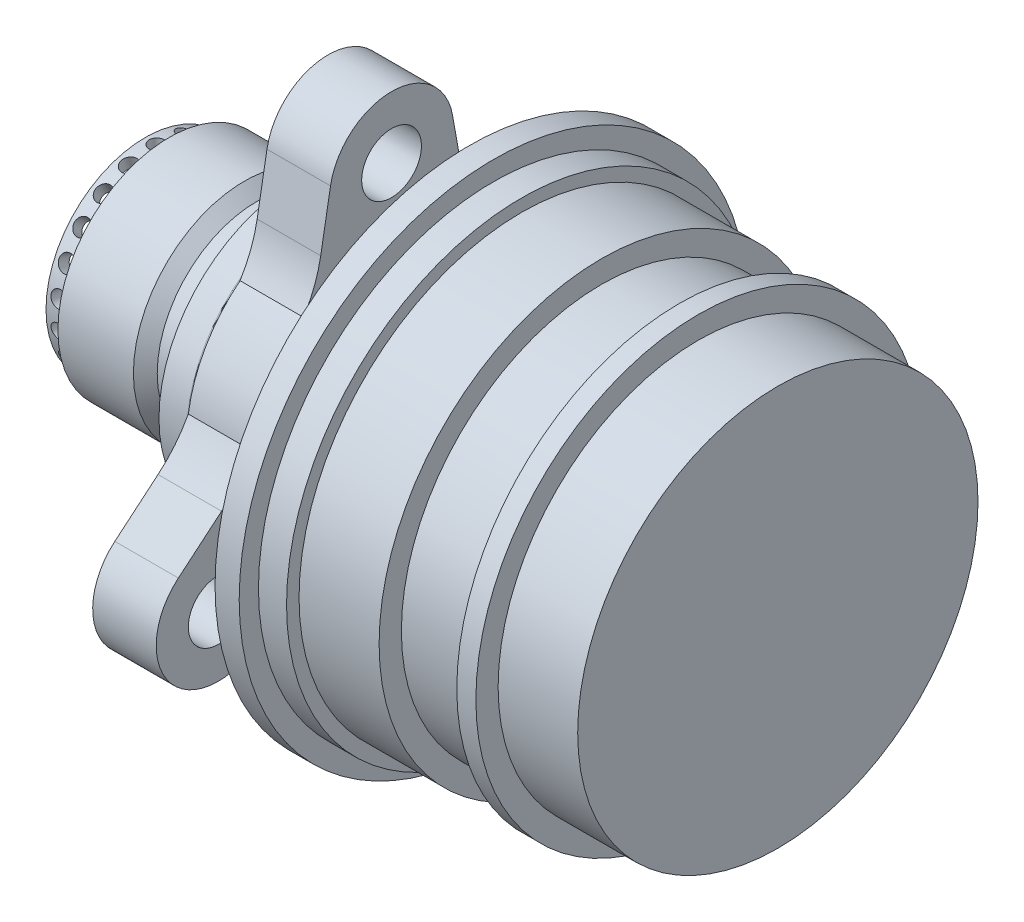
SolidWorks part; units mm, degrees
ref_plane "Front Plane" through (0, 0, 0) normal (0, 0, 1) x (1, 0, 0)
ref_plane "Top Plane" through (0, 0, 0) normal (0, 1, 0) x (1, 0, 0)
ref_plane "Right Plane" through (0, 0, 0) normal (1, 0, 0) x (0, 0, -1)
sketch "Sketch1" plane through (0, 0, 0) normal (0, 0, 1) x (1, 0, 0)
  line L2 (-605.6405, 247.65) -> (-589.6405, 247.65)
  line L3 (-644.3015, 255.5875) -> (-644.3015, 231.4258)
  line L5 (-570.3065, 243.1999) -> (-554.4065, 243.1999)
  line L9 (-605.6405, 247.65) -> (-605.6405, 250.15)
  line L11 (-554.4065, 243.1999) -> (-554.4065, 203.2)
  line L12 (-644.3015, 255.5875) -> (-631.6015, 255.5875)
  line L21 (-676.0515, 225.425) -> (-676.0515, 223.0437)
  line L22 (-676.0515, 223.0437) -> (-680.814, 223.0438)
  line L23 (-680.814, 223.0438) -> (-680.814, 220.6625)
  line L28 (-616.0785, 254) -> (-611.2525, 254)
  line L29 (-611.2525, 254) -> (-611.2525, 250.15)
  line L30 (-611.2525, 250.15) -> (-605.6405, 250.15)
  line L39 (-650.6515, 230.632) -> (-645.0952, 230.632)
  line L42 (-625.2515, 225.425) -> (-622.4285, 225.425)
  line L43 (-631.6015, 255.5875) -> (-631.6015, 231.775)
  line L44 (-616.0785, 254) -> (-616.0785, 231.775)
  line L45 (-655.414, 223.0437) -> (-658.589, 223.0437)
  line L46 (-658.589, 223.0437) -> (-660.9702, 225.425)
  line L47 (-650.6515, 227.8062) -> (-650.6515, 230.632)
  line L48 (-570.3065, 243.1999) -> (-570.3065, 247.65)
  line L50 (-574.1165, 247.65) -> (-574.1165, 243.1999)
  line L52 (-589.6405, 243.1999) -> (-589.6405, 247.65)
  line L53 (-660.9702, 225.425) -> (-676.0515, 225.425)
  line L54 (-680.814, 220.6625) -> (-618.6185, 220.6625)
  line L55 (-616.0785, 218.1225) -> (-616.0785, 203.2)
  line L56 (-616.0785, 203.2) -> (-554.4065, 203.2)
  line L57 (-618.6185, 220.6625) -> (-616.0785, 220.6625)
  line L58 (-616.0785, 220.6625) -> (-616.0785, 218.1225)
  line L59 (-574.1165, 247.65) -> (-570.3065, 247.65)
  line L60 (-589.6405, 243.1999) -> (-574.1165, 243.1999)
  arc A0 (-645.0952, 230.632) -> (-644.3015, 231.4258) centre (-645.0952, 231.4258) ccw
  arc A1 (-655.414, 223.0437) -> (-650.6515, 227.8062) centre (-655.414, 227.8062) ccw
  arc A2 (-622.4285, 225.425) -> (-616.0785, 231.775) centre (-622.4285, 231.775) ccw
  arc A3 (-631.6015, 231.775) -> (-625.2515, 225.425) centre (-625.2515, 231.775) ccw
  point P8 (-597.6405, 247.65)
  point P16 (-562.3565, 243.1999)
  point P32 (-613.6655, 254)
  dimension "D5" = 0.7937
  dimension "D10" = 4.7625
  dimension "D19" = 6.35
  dimension "D20" = 2.54
  dimension "D1" = 16
  dimension "D2" = 39.9999
  dimension "D3" = 15.9
  dimension "D4" = 12.7
  dimension "D6" = 17.4625
  dimension "D8" = 19.8438
  dimension "D9" = 27.432
  dimension "D11" = 4.7625
  dimension "D12" = 25.4
  dimension "D13" = 135
  dimension "D14" = 3.175
  dimension "D15" = 22.225
  dimension "D16" = 52.3875
  dimension "D17" = 4.826
  dimension "D18" = 50.8
  dimension "D21" = 2.5
  dimension "D22" = 44.45
  dimension "D23" = 5.612
  dimension "D27" = 3.81
  dimension "D28" = 2.54
revolve "Revolve1" add sketch "Sketch1" angle 360 about L56
sketch "Sketch2" plane through (-644.3015, 0, 0) normal (-1, 0, 0) x (0, 0, 1)
  line L0 (0, 243.2) -> (0, 203.2) construction
  line L1 (0, 203.2) -> (34.641, 183.2) construction
  line L2 (34.641, 183.2) -> (0, 203.2) construction
  line L3 (0, 203.2) -> (-34.641, 183.2) construction
  circle A0 centre (0, 203.2) radius 40 construction
  circle A1 centre (0, 243.2) radius 5.975
  circle A2 centre (-34.641, 183.2) radius 5.975
  circle A3 centre (34.641, 183.2) radius 5.975
  dimension "D1" = 80
  dimension "D2" = 11.95
  dimension "D5" = 11.95
  dimension "D6" = 11.95
  dimension "D3" = 120
  dimension "D4" = 120
extrude "Cut-Extrude1" cut sketch "Sketch2" against normal up to next
sketch "Sketch4" plane through (-644.3015, 0, 0) normal (-1, 0, 0) x (0, 0, 1)
  line L0 (-14.1576, 234.2452) -> (-12.1993, 245.3511)
  line L1 (12.1993, 245.3511) -> (14.1576, 234.2452)
  line L2 (0, 243.2) -> (0, 203.2) construction
  line L3 (33.9647, 199.9382) -> (42.6035, 192.6894)
  line L4 (30.4042, 171.5596) -> (19.8071, 175.4166)
  line L5 (-19.8071, 175.4166) -> (-30.4042, 171.5596)
  line L6 (-42.6035, 192.6894) -> (-33.9647, 199.9382)
  arc A0 (-5.774, 176.3795) -> (5.774, 176.3795) centre (0, 203.2) ccw
  arc A1 (-12.1993, 245.3511) -> (12.1993, 245.3511) centre (0, 243.2) cw
  arc A2 (14.1576, 234.2452) -> (20.3402, 221.6107) centre (39.1717, 238.6558) ccw
  arc A3 (-14.1576, 234.2452) -> (-20.3402, 221.6107) centre (-39.1717, 238.6558) cw
  arc A4 (33.9647, 199.9382) -> (26.1143, 211.6098) centre (50.2915, 219.3958) cw
  arc A5 (42.6035, 192.6894) -> (30.4042, 171.5596) centre (34.641, 183.2) cw
  arc A6 (19.8071, 175.4166) -> (5.774, 176.3795) centre (11.1198, 151.5484) ccw
  arc A7 (-19.8071, 175.4166) -> (-5.774, 176.3795) centre (-11.1198, 151.5484) cw
  arc A8 (-30.4042, 171.5596) -> (-42.6035, 192.6894) centre (-34.641, 183.2) cw
  arc A9 (-33.9647, 199.9382) -> (-26.1143, 211.6098) centre (-50.2915, 219.3958) ccw
  arc A10 (-20.3402, 221.6107) -> (-26.1143, 211.6098) centre (0, 203.2) ccw
  arc A11 (26.1143, 211.6098) -> (20.3402, 221.6107) centre (0, 203.2) ccw
  circle A12 centre (0, 203.2) radius 53.34
  point P29 (0, 203.2)
  point P31 (0, 203.2)
  point P33 (0, 203.2)
  circle M23 centre (0, 203.2) radius 28.2258
  dimension "D1" = 106.68
  dimension "D4" = 27.435
  dimension "D5" = 25.4
  dimension "D6" = 12.3875
  dimension "D2" = 20
  dimension "D3" = 8.4098
  dimension "D7" = 11.2772
  dimension "D8" = 20
extrude "Cut-Extrude2" cut sketch "Sketch4" against normal up to next contours A1 A12 A8 L6 A9 A3 L0 M23 | A5 A12 A1 L1 A2 A4 L3 M23 | A8 A12 A5 L4 A6 A7 L5 M23
ref_plane "Plane1" through (0, 223.0437, 0) normal (0, 1, 0) x (1, 0, 0)
sketch "Sketch5" plane through (0, 223.0437, 0) normal (0, 1, 0) x (1, 0, 0)
  line L0 (-680.814, 0) -> (-676.0515, 0) construction
  circle A0 centre (-678.4327, 0) radius 1.5875
  dimension "D1" = 3.175
extrude "Cut-Extrude3" cut sketch "Sketch5" against normal up to next
pattern_circular "CirPattern1" count 22 over 360 about axis through (-616.0785, 203.2, 0) along (-1, 0, 0) of "Cut-Extrude3"
